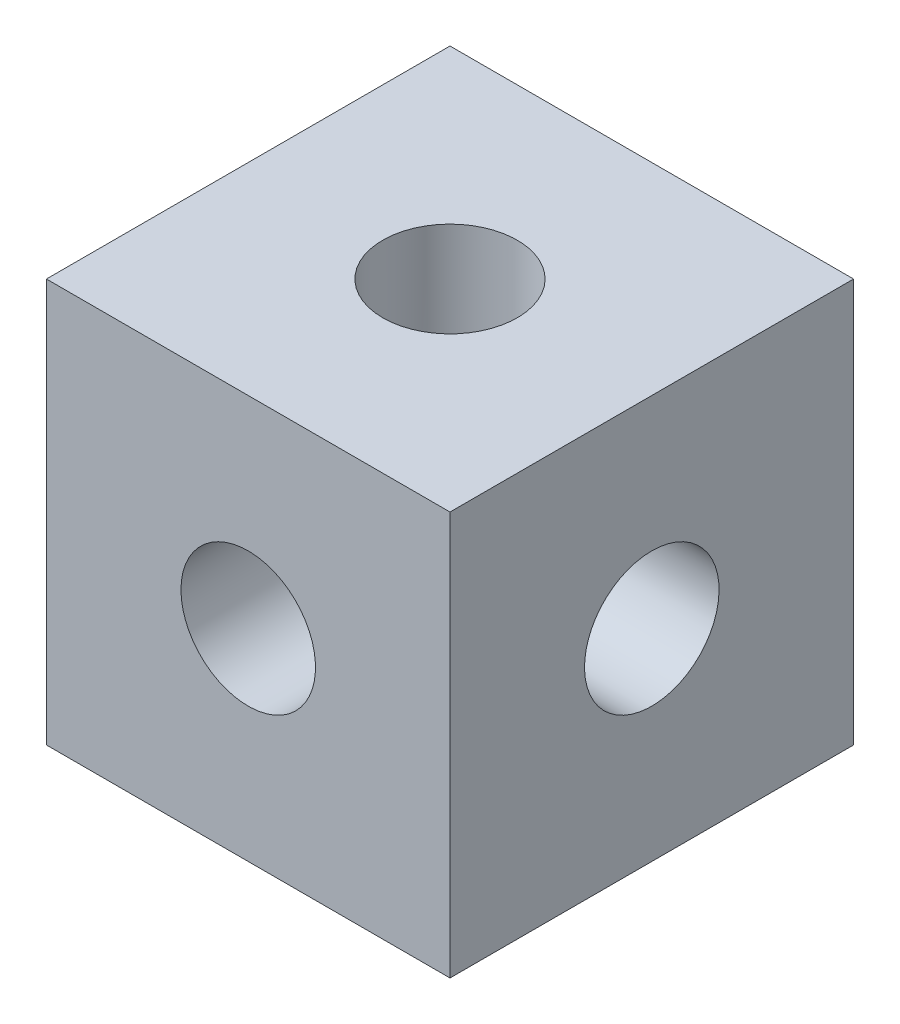
SolidWorks part; units mm, degrees
material "6061 合金"
ref_plane "前视基准面" through (0, 0, 0) normal (0, 0, 1) x (1, 0, 0)
ref_plane "上视基准面" through (0, 0, 0) normal (0, 1, 0) x (1, 0, 0)
ref_plane "右视基准面" through (0, 0, 0) normal (1, 0, 0) x (0, 0, -1)
other "Configuration Table"
sketch "草图1" plane through (0, 0, 0) normal (0, 0, 1) x (1, 0, 0)
  line L1 (0, 0) -> (12, 0)
  line L2 (0, 0) -> (0, -12)
  line L3 (0, -12) -> (12, -12)
  line L4 (12, 0) -> (12, -12)
  dimension "D1" = 12
  dimension "D2" = 12
extrude "凸台-拉伸1" add sketch "草图1" along normal blind 12
sketch "草图2" plane through (12, 0, 0) normal (1, 0, 0) x (0, 0, -1)
  line L0 (-12, -6) -> (0, -6) construction
  line L1 (-12, -12) -> (-12, 0) construction
  line L2 (0, -12) -> (0, 0) construction
  circle A0 centre (-6, -6) radius 2
  dimension "D3" = 4
extrude "切除-拉伸1" cut sketch "草图2" against normal through all
sketch "草图3" plane through (0, 0, 0) normal (0, 1, 0) x (1, 0, 0)
  line L0 (6, 0) -> (6, -12) construction
  line L1 (12, 0) -> (0, 0) construction
  line L2 (12, -12) -> (0, -12) construction
  circle A1 centre (6, -6) radius 2
  dimension "D1" = 4
extrude "切除-拉伸2" cut sketch "草图3" against normal through all
sketch "草图4" plane through (0, 0, 0) normal (0, 0, -1) x (-1, 0, 0)
  line L0 (-12, -6) -> (0, -6) construction
  line L1 (-12, -12) -> (-12, 0) construction
  line L2 (0, 0) -> (0, -12) construction
  circle A0 centre (-6, -6) radius 2
  dimension "D1" = 4
extrude "切除-拉伸3" cut sketch "草图4" against normal through all
